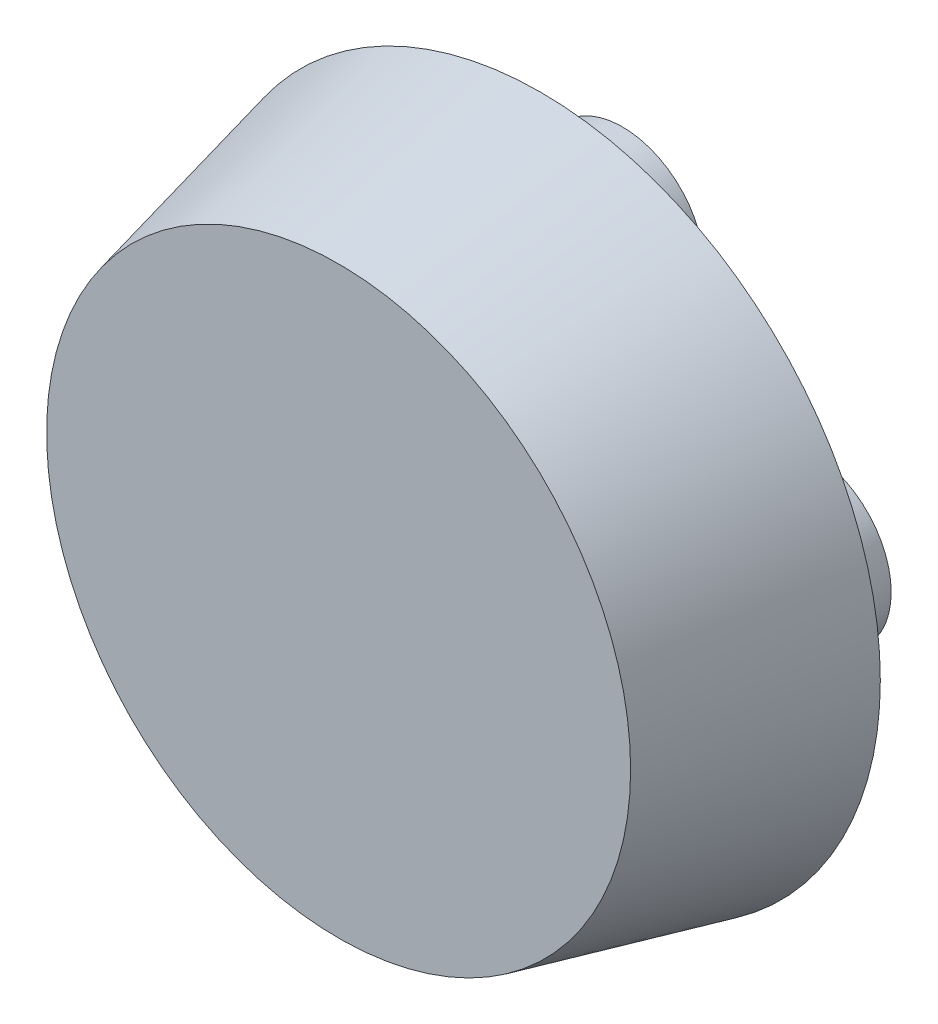
SolidWorks part; units mm, degrees
ref_plane "Front Plane" through (0, 0, 0) normal (0, 0, 1) x (1, 0, 0)
ref_plane "Top Plane" through (0, 0, 0) normal (0, 1, 0) x (1, 0, 0)
ref_plane "Right Plane" through (0, 0, 0) normal (1, 0, 0) x (0, 0, -1)
sketch "Big Plug Sketch" plane through (0, 0, 0) normal (1, 0, 0) x (0, 0, -1)
  line L0 (594.1751, -558.8643) -> (886.5863, -558.8643) construction
  line L1 (0, 0) -> (531.6016, 125) construction
  line L2 (0, 0) -> (531.6016, 0) construction
  line L3 (531.6016, 125) -> (531.6016, 0)
  line L4 (531.6016, 125) -> (618.1413, 145.3488)
  line L5 (531.6016, 0) -> (635, 0)
  arc A1 (635, 0) -> (618.1413, 145.3488) centre (0, 0) ccw
  dimension "D1" = 546.1
  dimension "D2" = 635
  dimension "D3" = 125
revolve "Big Plug" add sketch "Big Plug Sketch" angle 360 about L2
ref_plane "Big Plug Subsurface Plane" through (0, 0, -618.1413) normal (0, 0, 1) x (1, 0, 0)
sketch "Cables Sketch" plane through (0, 0, -618.1413) normal (0, 0, 1) x (1, 0, 0)
  line L0 (0, 145.3488) -> (0, -145.3488) construction
  line L1 (145.3488, 0) -> (-145.3488, 0) construction
  line L2 (0, 80) -> (0, 0) construction
  line L3 (0, 145.3488) -> (145.3488, 0) construction
  line L4 (145.3488, 0) -> (0, -145.3488) construction
  line L7 (72.6744, 72.6744) -> (0, 0) construction
  line L8 (0, 0) -> (72.6744, -72.6744) construction
  circle A0 centre (0, 0) radius 145.3488 construction
  circle A1 centre (0, 80) radius 35
  circle A2 centre (0, 80) radius 35
  circle A5 centre (80, 0) radius 35
  circle A6 centre (0, -80) radius 35
  circle A7 centre (-80, 0) radius 35
  point P12 (0, 0)
  dimension "D1" = 70
  dimension "D2" = 80
extrude "Cables" add sketch "Cables Sketch" against normal blind 35 from surface at 0 contours A1 | A5 | A6 | A7 starting at plane "Big Plug Subsurface Plane"
